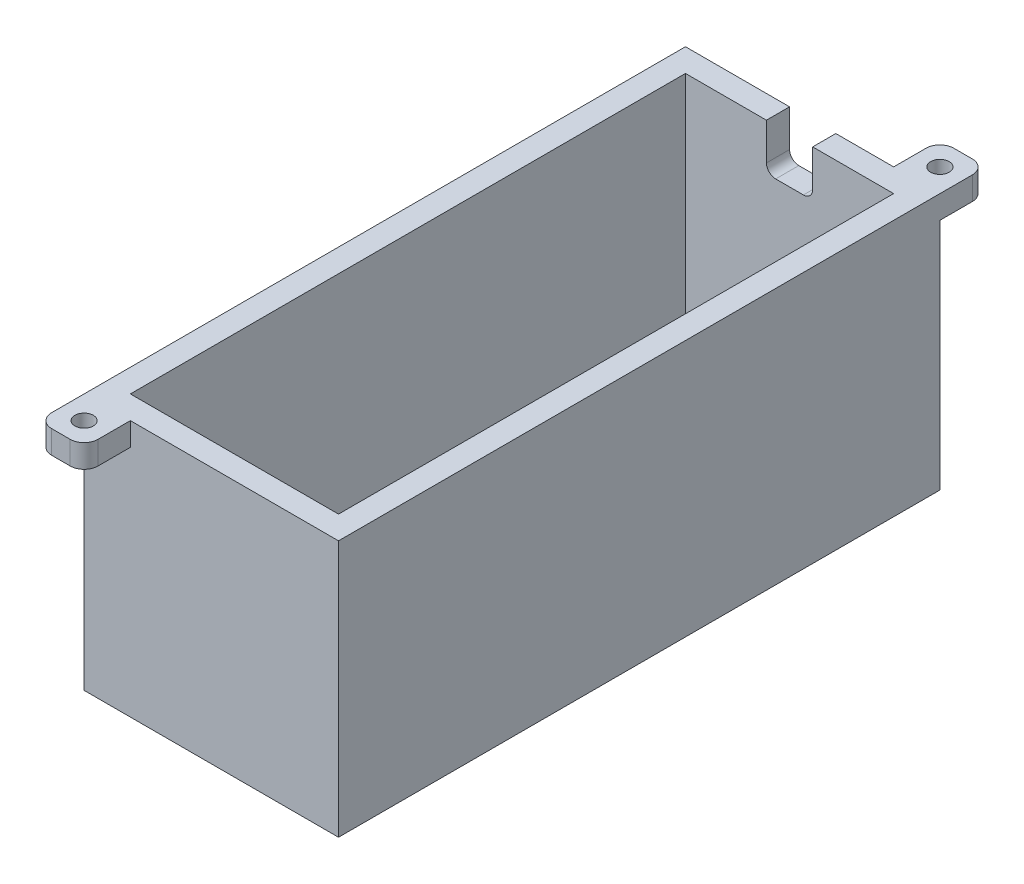
SolidWorks part; units mm, degrees
ref_plane "Front Plane" through (0, 0, 0) normal (0, 0, 1) x (1, 0, 0)
ref_plane "Top Plane" through (0, 0, 0) normal (0, 1, 0) x (1, 0, 0)
ref_plane "Right Plane" through (0, 0, 0) normal (1, 0, 0) x (0, 0, -1)
sketch "Sketch1" plane through (0, 0, 0) normal (0, 1, 0) x (1, 0, 0)
  line L0 (0, 0) -> (27.5, 0)
  line L1 (-55, 0) -> (55, 0) construction
  line L2 (0, 0) -> (0, 65)
  line L3 (0, -55) -> (0, 55) construction
  line L5 (-27.5, -65) -> (27.5, -65)
  line L6 (-27.5, -65) -> (-27.5, 65)
  line L7 (-27.5, 65) -> (27.5, 65)
  line L8 (27.5, -65) -> (27.5, 65)
  line L9 (-27.5, -65) -> (27.5, 65) construction
  line L10 (-27.5, 65) -> (27.5, -65) construction
extrude "Boss-Extrude1" add sketch "Sketch1" along normal blind 5 contours L5 L8 L0 L2 L7 L6 | L0 L8 L7 L2
sketch "Sketch2" plane through (0, 5, 0) normal (0, 1, 0) x (1, 0, 0)
  line L0 (0, 0) -> (0, 60)
  line L1 (0, -2.75) -> (0, 2.75) construction
  line L2 (0, 0) -> (22.5, 0)
  line L5 (-2.75, 0) -> (2.75, 0) construction
  line L7 (-22.5, -60) -> (22.5, -60)
  line L8 (-22.5, -60) -> (-22.5, 60)
  line L9 (-22.5, 60) -> (22.5, 60)
  line L10 (22.5, -60) -> (22.5, 60)
  line L11 (-22.5, -60) -> (22.5, 60) construction
  line L12 (-22.5, 60) -> (22.5, -60) construction
  line M7 (27.5, -65) -> (27.5, 65)
  line M8 (27.5, 65) -> (-27.5, 65)
  line M9 (-27.5, 65) -> (-27.5, -65)
  line M10 (-27.5, -65) -> (27.5, -65)
extrude "Boss-Extrude2" add sketch "Sketch2" along normal blind 50.5 contours L10 L7 L8 L9 M10 M7 M8 M9
sketch "Sketch3" plane through (0, 55.5, 0) normal (0, 1, 0) x (1, 0, 0)
  line L0 (27.5, 65) -> (27.5, 75)
  line L1 (27.5, 75) -> (17.5, 75)
  line L2 (17.5, 75) -> (17.5, 65)
  line L3 (27.5, 65) -> (-27.5, 65) construction
  line L4 (17.5, 65) -> (27.5, 65)
  line L5 (-27.5, -65) -> (-27.5, -75)
  line L6 (-27.5, -75) -> (-17.5, -75)
  line L7 (-17.5, -75) -> (-17.5, -65)
  line L8 (-27.5, -65) -> (27.5, -65) construction
  line L9 (-17.5, -65) -> (-27.5, -65)
extrude "Boss-Extrude4" add sketch "Sketch3" against normal blind 5
sketch "Sketch4" plane through (0, 50.5, 0) normal (0, -1, 0) x (1, 0, 0)
  line L0 (22.5, -75) -> (22.5, -70)
  line L1 (27.5, -75) -> (17.5, -75) construction
  line L2 (-22.5, 75) -> (-22.5, 70)
  line L3 (-27.5, 75) -> (-17.5, 75) construction
  circle A0 centre (22.5, -70) radius 2
  circle A1 centre (-22.5, 70) radius 2
extrude "Cut-Extrude1" cut sketch "Sketch4" against normal blind 5
fillet "Fillet1" radius 1 1 edges at (22.5, 50.5, -72)
fillet "Fillet2" radius 1 1 edges at (-22.5, 50.5, 68)
ref_plane "Plane1" through (27.5, 0, 65) normal (1, 0, 0) x (0, 0, -1)
sketch "Sketch6" plane through (0, 0, 0) normal (0, -1, 0) x (1, 0, 0)
  line L0 (0, 0) -> (19, 0)
  line L1 (30.25, 0) -> (-30.25, 0) construction
  line L2 (0, 0) -> (-19, 0)
  line L3 (0, 0) -> (0, 22.65)
  line L4 (0, -30.525) -> (0, 30.525) construction
  line L6 (-19, -22.65) -> (19, -22.65)
  line L7 (-19, -22.65) -> (-19, 22.65)
  line L8 (-19, 22.65) -> (19, 22.65)
  line L9 (19, -22.65) -> (19, 22.65)
  line L10 (-19, -22.65) -> (19, 22.65) construction
  line L11 (-19, 22.65) -> (19, -22.65) construction
extrude "Cut-Extrude2" cut sketch "Sketch6" against normal blind 5 contours L7 L6 L9 L8
fillet "Fillet3" radius 3 4 edges at (17.5, 53, -75) (27.5, 53, -75) (-17.5, 53, 75) (-27.5, 53, 75)
ref_plane "Plane2" through (-22.5, 55.5, 60) normal (0, -1, 0) x (-1, 0, 0)
sketch "Sketch8" plane through (0, 0, -65) normal (0, 0, -1) x (-1, 0, 0)
  line L0 (0, 55.5) -> (5, 55.5)
  line L3 (0, 30.525) -> (0, -30.525) construction
  line L4 (-17.5, 55.5) -> (27.5, 55.5) construction
  line L5 (0, 55.5) -> (-5, 55.5)
  line L6 (-5, 55.5) -> (-5, 45.5)
  line L7 (-5, 45.5) -> (5, 45.5)
  line L8 (5, 45.5) -> (5, 55.5)
extrude "Cut-Extrude3" cut sketch "Sketch8" against normal blind 5
fillet "Fillet4" radius 2 2 edges at (5, 45.5, -62.5) (-5, 45.5, -62.5)
